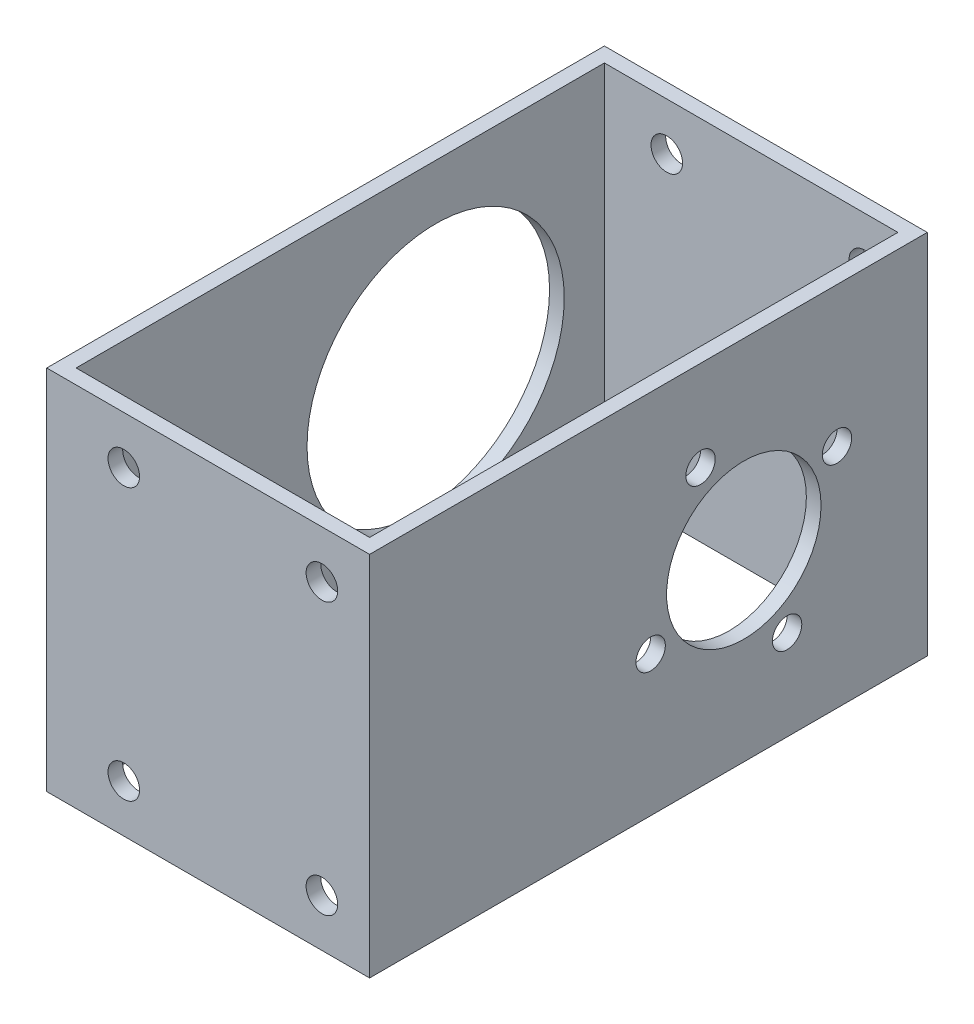
SolidWorks part; units mm, degrees
material "1060 合金"
ref_plane "前视基准面" through (0, 0, 0) normal (0, 0, 1) x (1, 0, 0)
ref_plane "上视基准面" through (0, 0, 0) normal (0, 1, 0) x (1, 0, 0)
ref_plane "右视基准面" through (0, 0, 0) normal (1, 0, 0) x (0, 0, -1)
other "电机1号"
sketch "草图1" plane through (0, 0, 0) normal (0, 1, 0) x (1, 0, 0)
  line L0 (2, -2) -> (42, -2)
  line L1 (0, 0) -> (44, 0)
  line L2 (0, 0) -> (0, -76)
  line L3 (0, -76) -> (44, -76)
  line L4 (44, 0) -> (44, -76)
  line L5 (42, -2) -> (42, -74)
  line L6 (2, -74) -> (42, -74)
  line L7 (2, -2) -> (2, -74)
  dimension "D1" = 44
  dimension "D2" = 76
  dimension "D3" = 2
extrude "凸台-拉伸1" add sketch "草图1" along normal blind 50
sketch "草图2" plane through (0, 0, 0) normal (0, 0, -1) x (-1, 0, 0)
  line L1 (-44, 0) -> (0, 0) construction
  line L2 (-44, 50) -> (-44, 0) construction
  line L3 (-44, 50) -> (0, 50) construction
  circle A0 centre (-10.5, 6.5) radius 2.15
  circle A1 centre (-37.5, 6.5) radius 2.15
  circle A2 centre (-37.5, 43.5) radius 2.15
  circle A3 centre (-10.5, 43.5) radius 2.15
  dimension "D1" = 2
  dimension "D4" = 6.5
  dimension "D8" = 6.5
  dimension "D5" = 6.5
  dimension "D9" = 6.5
extrude "切除-拉伸1" cut sketch "草图2" against normal through all
sketch "草图3" plane through (0, 0, 0) normal (-1, 0, 0) x (0, 0, 1)
  line L0 (0, 50) -> (0, 0) construction
  line L3 (0, 50) -> (76, 50) construction
  circle A0 centre (25, 25) radius 17.525
  dimension "D1" = 35.05
  dimension "D2" = 25
  dimension "D3" = 25
extrude "切除-拉伸2" cut sketch "草图3" against normal up to next
sketch "草图4" plane through (44, 0, 0) normal (1, 0, 0) x (0, 0, -1)
  line L0 (0, 50) -> (0, 0) construction
  line L1 (-76, 0) -> (0, 0) construction
  line L2 (-25, 25) -> (0, 25) construction
  circle A0 centre (-25, 25) radius 10.525
  point P27 (-25, 25)
  dimension "D1" = 21.05
  dimension "D2" = 25
  dimension "D3" = 25
extrude "切除-拉伸3" cut sketch "草图4" against normal up to next
sketch "草图5" plane through (44, 0, 0) normal (1, 0, 0) x (0, 0, -1)
  line L0 (-50, 7.4) -> (0, 7.4) construction
  line L2 (0, 50) -> (0, 0) construction
  circle A0 centre (-17.1, 13.4419) radius 2
  circle A1 centre (-25, 25) radius 10.525 construction
  circle A2 centre (-36.5581, 17.1) radius 2
  circle A3 centre (-32.9, 36.5581) radius 2
  circle A4 centre (-13.4419, 32.9) radius 2
  circle A5 centre (-25, 25) radius 17.6 construction
  point P13 (-25, 25)
  point P19 (-25, 7.4)
  dimension "D1" = 4
  dimension "D4" = 35.2
  dimension "D2" = 14
  dimension "D5" = 25.5
  dimension "D3" = 4
extrude "切除-拉伸5" [suppressed] cut sketch "草图5" against normal blind 10
sketch "草图7" plane through (44, 0, 0) normal (1, 0, 0) x (0, 0, -1)
  line L0 (-50, 7.4) -> (0, 7.4) construction
  line L1 (0, 50) -> (0, 0) construction
  circle A0 centre (-25, 25) radius 17.6 construction
  circle A1 centre (-14.1931, 33.9) radius 2
  circle A2 centre (-16.1, 14.1931) radius 2
  circle A3 centre (-35.8069, 16.1) radius 2
  circle A4 centre (-33.9, 35.8069) radius 2
  point P10 (-25, 7.4)
  point P19 (-25, 25)
  dimension "D1" = 35.2
  dimension "D2" = 4
  dimension "D3" = 14
  dimension "D5" = 26.5
  dimension "D4" = 4
extrude "电机2号" [suppressed] cut sketch "草图7" against normal blind 10
sketch "草图8" plane through (44, 0, 0) normal (1, 0, 0) x (0, 0, -1)
  line L0 (-50, 7.4) -> (0, 7.4) construction
  circle A0 centre (-25, 25) radius 17.6 construction
  circle A1 centre (-13.8, 33.4) radius 2
  circle A2 centre (-16.6, 13.8) radius 2
  circle A3 centre (-36.2, 16.6) radius 2
  circle A4 centre (-33.4, 36.2) radius 2
  point P8 (-25, 7.4)
  point P17 (-25, 25)
  dimension "D1" = 35.2
  dimension "D2" = 4
  dimension "D5" = 26
  dimension "D3" = 14
  dimension "D4" = 4
extrude "电机3号" [suppressed] cut sketch "草图8" against normal blind 10
sketch "草图9" plane through (44, 0, 0) normal (1, 0, 0) x (0, 0, -1)
  line L0 (-50, 7.4) -> (0, 7.4) construction
  line L1 (0, 50) -> (0, 0) construction
  circle A0 centre (-25, 25) radius 17.6 construction
  circle A1 centre (-11.0004, 24.9) radius 2
  circle A2 centre (-25.1, 11.0004) radius 2
  circle A3 centre (-38.9996, 25.1) radius 2
  circle A4 centre (-24.9, 38.9996) radius 2
  point P10 (-25, 7.4)
  point P19 (-25, 25)
  dimension "D1" = 4
  dimension "D2" = 35.2
  dimension "D3" = 14
  dimension "D5" = 17.5
  dimension "D4" = 4
extrude "电机4号" [suppressed] cut sketch "草图9" against normal blind 10
sketch "草图10" plane through (44, 0, 0) normal (1, 0, 0) x (0, 0, -1)
  line L0 (-50, 7.4) -> (0, 7.4) construction
  circle A0 centre (-25, 25) radius 17.6 construction
  circle A1 centre (-11.029, 25.9) radius 2
  circle A2 centre (-24.1, 11.029) radius 2
  circle A3 centre (-38.971, 24.1) radius 2
  circle A4 centre (-25.9, 38.971) radius 2
  point P8 (-25, 7.4)
  point P17 (-25, 25)
  dimension "D1" = 35.2
  dimension "D2" = 4
  dimension "D3" = 14
  dimension "D5" = 18.5
  dimension "D4" = 4
extrude "电机5号" [suppressed] cut sketch "草图10" against normal blind 10
sketch "草图11" plane through (44, 0, 0) normal (1, 0, 0) x (0, 0, -1)
  line L0 (-50, 7.4) -> (0, 7.4) construction
  line L1 (0, 50) -> (0, 0) construction
  circle A0 centre (-25, 25) radius 17.6 construction
  circle A1 centre (-17.4, 36.7576) radius 2
  circle A2 centre (-13.2424, 17.4) radius 2
  circle A3 centre (-32.6, 13.2424) radius 2
  circle A4 centre (-36.7576, 32.6) radius 2
  point P10 (-25, 7.4)
  point P19 (-25, 25)
  dimension "D1" = 35.2
  dimension "D2" = 4
  dimension "D3" = 14
  dimension "D5" = 10
  dimension "D4" = 4
extrude "电机6号" [suppressed] cut sketch "草图11" against normal blind 10
sketch "草图12" plane through (44, 0, 0) normal (1, 0, 0) x (0, 0, -1)
  line L0 (-50, 7.4) -> (0, 7.4) construction
  line L1 (0, 50) -> (0, 0) construction
  circle A0 centre (-25, 25) radius 17.6 construction
  circle A1 centre (-12.3039, 30.9) radius 2
  circle A2 centre (-19.1, 12.3039) radius 2
  circle A3 centre (-37.6961, 19.1) radius 2
  circle A4 centre (-30.9, 37.6961) radius 2
  point P10 (-25, 7.4)
  point P19 (-25, 25)
  dimension "D1" = 4
  dimension "D2" = 35.2
  dimension "D3" = 14
  dimension "D5" = 23.5
  dimension "D4" = 4
extrude "电机7号" cut sketch "草图12" against normal blind 10
